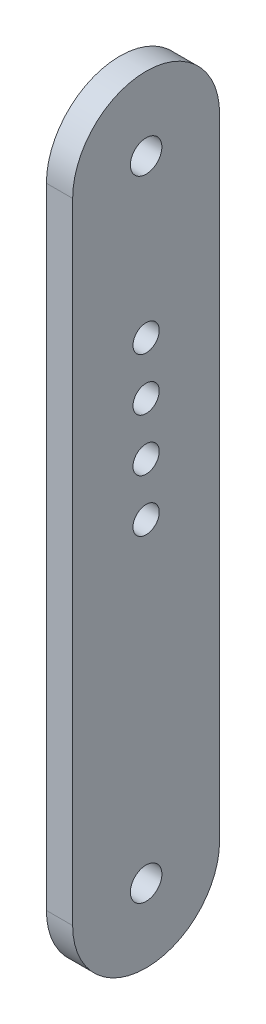
SolidWorks part; units mm, degrees
material "Acrylic (Medium-high impact)"
ref_plane "Ground" through (0, 0, 0) normal (0, 0, 1) x (1, 0, 0)
ref_plane "Right" through (0, 0, 0) normal (0, 1, 0) x (1, 0, 0)
ref_plane "Front" through (0, 0, 0) normal (1, 0, 0) x (0, 0, -1)
sketch "Sketch1" plane through (0, 0, 0) normal (1, 0, 0) x (0, 0, -1)
  line L0 (0, 0) -> (0, 60) construction
  line L1 (-7, 0) -> (-7, 60)
  line L2 (7, 0) -> (7, 60)
  arc A0 (-7, 0) -> (7, 0) centre (0, 0) ccw
  arc A1 (7, 60) -> (-7, 60) centre (0, 60) ccw
  circle A2 centre (0, 0) radius 1.5
  circle A3 centre (0, 60) radius 1.5
  circle A4 centre (0, 45) radius 1.25
  circle A8 centre (0, 40) radius 1.25
  circle A9 centre (0, 35) radius 1.25
  circle A10 centre (0, 30) radius 1.25
  point P3 (0, 30)
  dimension "D2" = 3
  dimension "D3" = 7
  dimension "D5" = 2.5
  dimension "D4" = 15
  dimension "D1" = 60
  dimension "D6" = 4
extrude "Boss-Extrude1" add sketch "Sketch1" along normal blind 2.5
